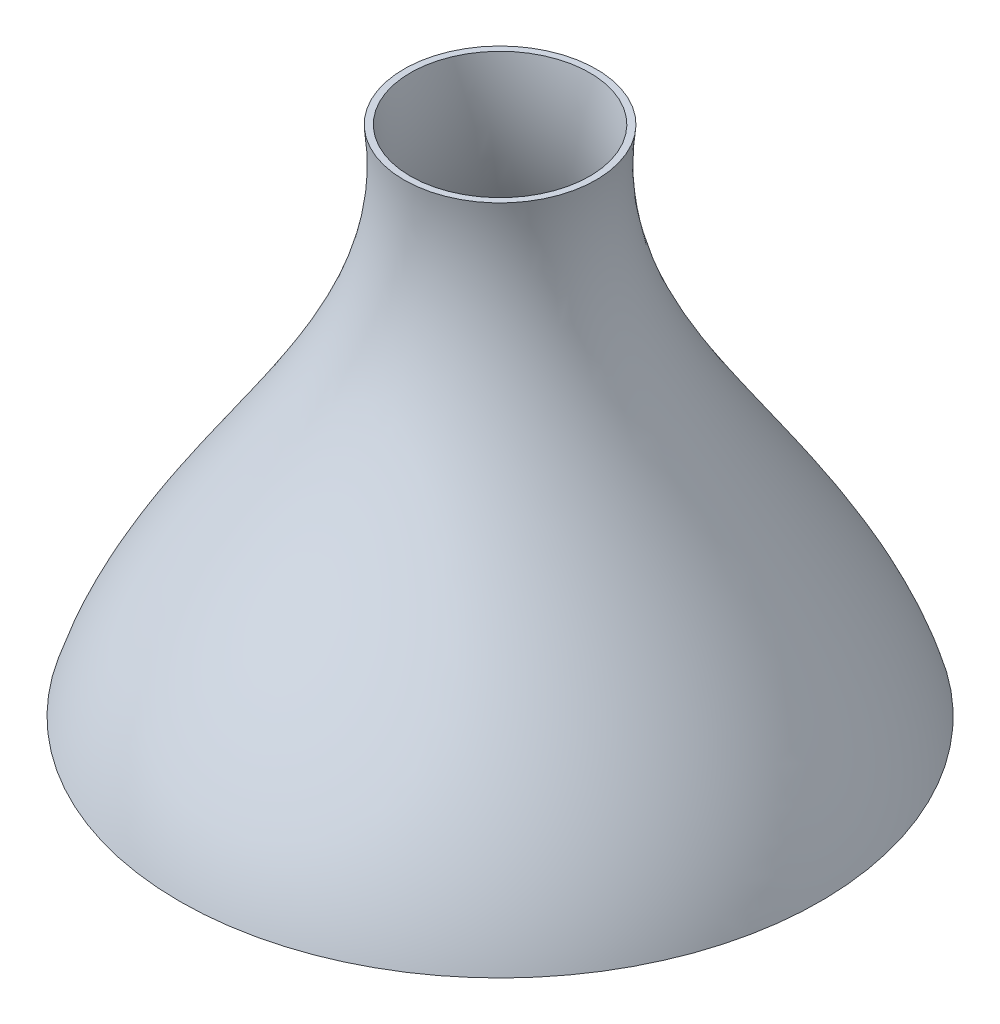
SolidWorks part; units mm, degrees
ref_plane "前视基准面" through (0, 0, 0) normal (0, 0, 1) x (1, 0, 0)
ref_plane "上视基准面" through (0, 0, 0) normal (0, 1, 0) x (1, 0, 0)
ref_plane "右视基准面" through (0, 0, 0) normal (1, 0, 0) x (0, 0, -1)
sketch "草图1" plane through (0, 0, 0) normal (0, 0, 1) x (1, 0, 0)
  line L0 (0, 46.1845) -> (0, -33.8155)
  line L1 (0, 46.1845) -> (15, 46.1845)
  line L2 (0, -33.8155) -> (50, -33.8155)
  line L5 (0, 46.1845) -> (0, 26.2745)
  spline S0 degree 3 poles (15, 46.1845) (11.0527, 14.8644) (42.0053, -6.7343) (50, -33.8155) knots 0 0 0 0 1 1 1 1
  dimension "D1" = 80
  dimension "D2" = 15
  dimension "D3" = 50
revolve "旋转1" add sketch "草图1" angle 360 about L0
shell "抽壳1" thickness 1
sketch "草图2" plane through (0, -33.8155, 0) normal (0, -1, 0) x (1, 0, 0)
  circle A0 centre (0, 0) radius 49.5
  dimension "D1" = 99
extrude "切除-拉伸1" cut sketch "草图2" against normal blind 1
